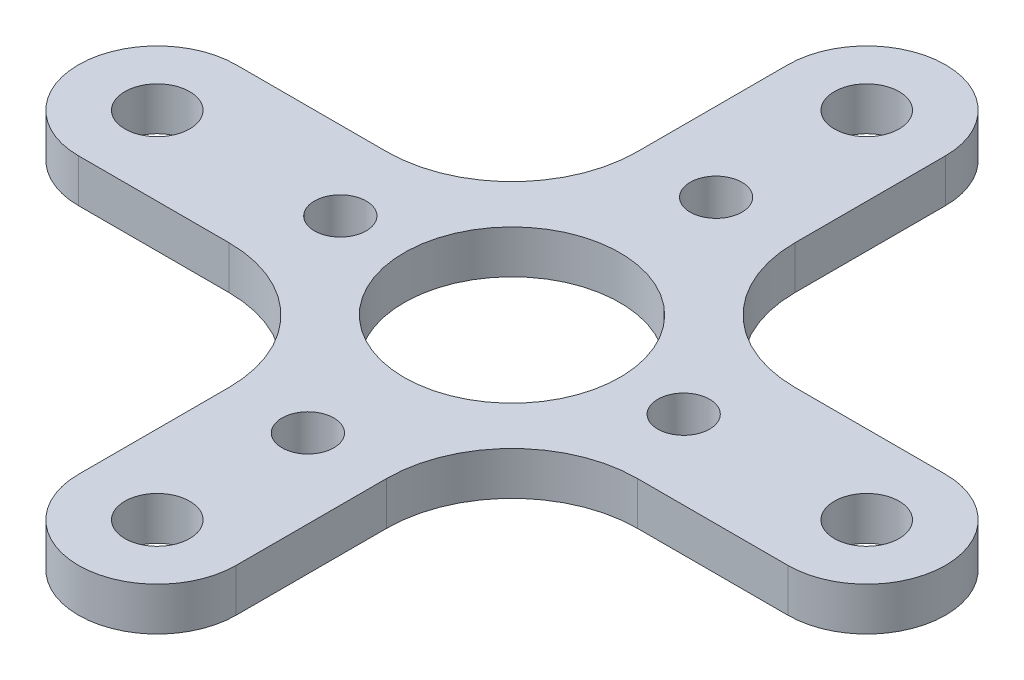
SolidWorks part; units mm, degrees
ref_plane "Front Plane" through (0, 0, 0) normal (0, 0, 1) x (1, 0, 0)
ref_plane "Top Plane" through (0, 0, 0) normal (0, 1, 0) x (1, 0, 0)
ref_plane "Right Plane" through (0, 0, 0) normal (1, 0, 0) x (0, 0, -1)
sketch "Sketch1" plane through (0, 0, 0) normal (0, 1, 0) x (1, 0, 0)
  line L0 (-1.8073, 20.1252) -> (-8.7823, 20.1252)
  line L1 (-18.2323, 27.4252) -> (-18.2323, 20.1252) construction
  line L2 (-21.8823, 40.2002) -> (-21.8823, 33.2252)
  line L3 (-1.8073, 27.4252) -> (-8.7823, 27.4252)
  line L4 (-14.5823, 40.2002) -> (-14.5823, 33.2252)
  line L5 (-21.8823, 23.7752) -> (-14.5823, 23.7752) construction
  line L6 (-24.9823, 23.7752) -> (-24.9823, 22.7752) construction
  line L7 (-11.4823, 23.7752) -> (-11.4823, 22.7752) construction
  line L8 (-27.3823, 23.7752) -> (-30.6073, 23.7752) construction
  line L9 (-9.0823, 23.7752) -> (-5.8573, 23.7752) construction
  line L10 (-18.2323, 32.0252) -> (-19.2323, 32.0252) construction
  line L11 (-18.2323, 15.5252) -> (-19.2323, 15.5252) construction
  line L12 (-18.2323, 13.1252) -> (-18.2323, 11.4002) construction
  line L13 (-18.2323, 34.4252) -> (-18.2323, 36.1502) construction
  line L14 (-10.2823, 23.7752) -> (-26.1823, 23.7752) construction
  line L16 (-17.0323, 33.2252) -> (-14.5823, 33.2252) construction
  line L17 (-8.7823, 24.9752) -> (-8.7823, 27.4252) construction
  line L21 (-27.6823, 27.4252) -> (-34.6573, 27.4252)
  line L23 (-21.8823, 14.3252) -> (-21.8823, 7.3502)
  line L24 (-27.6823, 20.1252) -> (-34.6573, 20.1252)
  line L25 (-14.5823, 14.3252) -> (-14.5823, 7.3502)
  arc A0 (-21.8823, 40.2002) -> (-14.5823, 40.2002) centre (-18.2323, 40.2002) cw
  arc A1 (-21.8823, 7.3502) -> (-14.5823, 7.3502) centre (-18.2323, 7.3502) ccw
  circle A2 centre (-18.2323, 40.2002) radius 1.5
  circle A3 centre (-18.2323, 7.3502) radius 1.5
  arc A4 (-1.8073, 27.4252) -> (-1.8073, 20.1252) centre (-1.8073, 23.7752) cw
  circle A5 centre (-34.6573, 23.7752) radius 1.5
  arc A6 (-34.6573, 27.4252) -> (-34.6573, 20.1252) centre (-34.6573, 23.7752) ccw
  circle A7 centre (-1.8073, 23.7752) radius 1.5
  circle A8 centre (-26.1823, 23.7752) radius 1.2
  circle A9 centre (-10.2823, 23.7752) radius 1.2
  circle A10 centre (-18.2323, 33.2252) radius 1.2
  circle A11 centre (-18.2323, 14.3252) radius 1.2
  circle A12 centre (-18.2323, 23.7752) radius 5
  arc A13 (-14.5823, 33.2252) -> (-8.7823, 27.4252) centre (-8.7823, 33.2252) ccw
  arc A14 (-8.7823, 20.1252) -> (-14.5823, 14.3252) centre (-8.7823, 14.3252) ccw
  arc A15 (-21.8823, 14.3252) -> (-27.6823, 20.1252) centre (-27.6823, 14.3252) ccw
  arc A16 (-27.6823, 27.4252) -> (-21.8823, 33.2252) centre (-27.6823, 33.2252) ccw
  dimension "D1" = 2.4
  dimension "D2" = 2.4
  dimension "D3" = 16.5
extrude "Extrude1" add sketch "Sketch1" along normal blind 2
